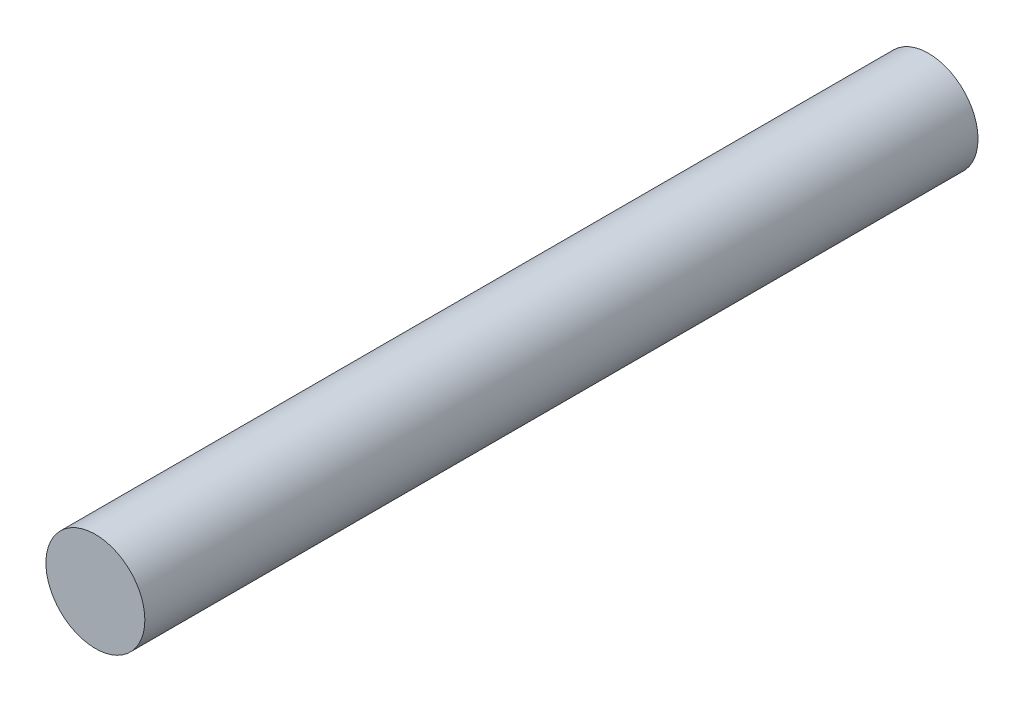
SolidWorks part; units mm, degrees
ref_plane "Front Plane" through (0, 0, 0) normal (0, 0, 1) x (1, 0, 0)
ref_plane "Top Plane" through (0, 0, 0) normal (0, 1, 0) x (1, 0, 0)
ref_plane "Right Plane" through (0, 0, 0) normal (1, 0, 0) x (0, 0, -1)
sketch "Sketch1" plane through (0, 0, 0) normal (0, 0, 1) x (1, 0, 0)
  circle A0 centre (0, 0) radius 1.425
  dimension "D1" = 2.85
extrude "Boss-Extrude1" add sketch "Sketch1" along normal blind 24
